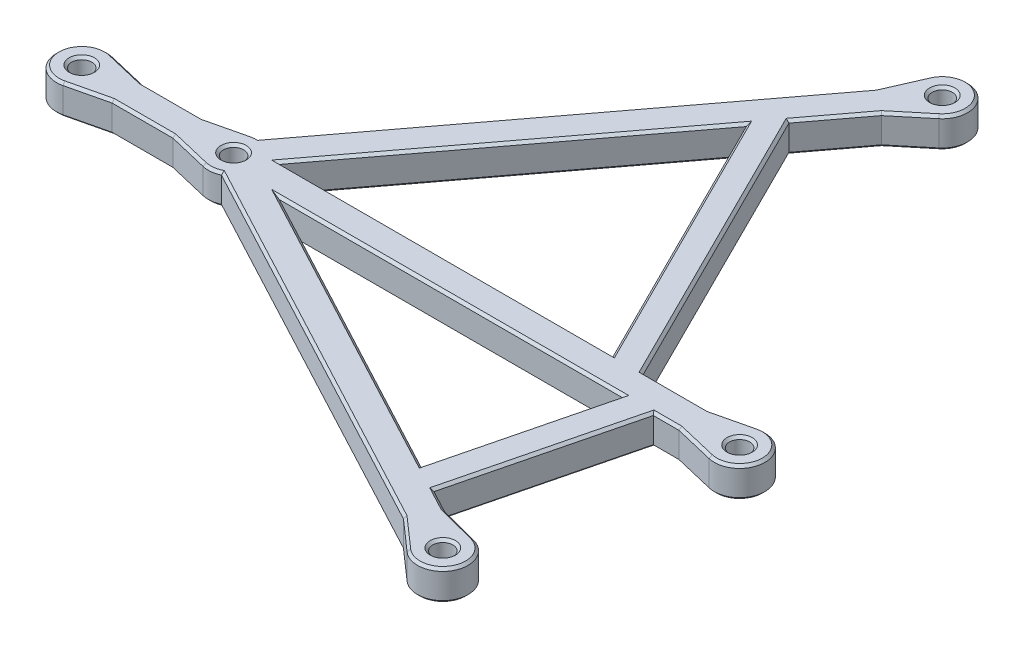
SolidWorks part; units mm, degrees
ref_plane "前视基准面" through (0, 0, 0) normal (0, 0, 1) x (1, 0, 0)
ref_plane "上视基准面" through (0, 0, 0) normal (0, 1, 0) x (1, 0, 0)
ref_plane "右视基准面" through (0, 0, 0) normal (1, 0, 0) x (0, 0, -1)
other "Configuration Table"
sketch "草图1" plane through (0, 0, 0) normal (0, 1, 0) x (1, 0, 0)
  line L0 (0, 0) -> (15, 0) construction
  line L1 (15, 0) -> (65, 0) construction
  line L2 (2, 1.5) -> (13, 1.5)
  line L3 (2, -1.5) -> (13, -1.5)
  line L4 (17, 1.5) -> (63, 1.5)
  line L5 (17, -1.5) -> (63, -1.5)
  arc A0 (2, 1.5) -> (2, -1.5) centre (0, 0) ccw
  arc A1 (17, 1.5) -> (13, 1.5) centre (15, 0) ccw
  arc A2 (63, -1.5) -> (63, 1.5) centre (65, 0) ccw
  arc A3 (13, -1.5) -> (17, -1.5) centre (15, 0) ccw
  circle A4 centre (0, 0) radius 1
  circle A5 centre (15, 0) radius 1
  circle A6 centre (65, 0) radius 1
  dimension "D1" = 5
  dimension "D3" = 5
  dimension "D5" = 5
  dimension "D6" = 2
  dimension "D7" = 2
  dimension "D9" = 2
  dimension "D2" = 15
  dimension "D4" = 50
  dimension "D8" = 3
extrude "凸台-拉伸2" add sketch "草图1" along normal blind 3
sketch "草图3" plane through (0, 0, 0) normal (0, 1, 0) x (1, 0, 0)
  line L0 (15, 0) -> (65, 0) construction
  line L1 (15, 0) -> (45.0908, 39.9318) construction
  line L2 (15, 0) -> (59.1474, -23.4736) construction
  line L3 (15.0057, 2.5) -> (42.6892, 39.2372)
  line L4 (17.4016, 0.6945) -> (45.0851, 37.4318)
  line L5 (16.0617, -2.2634) -> (56.6773, -23.8591)
  line L6 (17.4701, 0.3855) -> (58.0857, -21.2102)
  arc A0 (17.4701, 0.3855) -> (17.4016, 0.6945) centre (15, 0) ccw
  arc A1 (45.0851, 37.4318) -> (42.6892, 39.2372) centre (45.0908, 39.9318) ccw
  arc A2 (56.6773, -23.8591) -> (58.0857, -21.2102) centre (59.1474, -23.4736) ccw
  arc A3 (15.0057, 2.5) -> (16.0617, -2.2634) centre (15, 0) ccw
  circle A4 centre (59.1474, -23.4736) radius 1
  circle A5 centre (45.0908, 39.9318) radius 1
  circle A6 centre (15, 0) radius 1
  dimension "D1" = 5
  dimension "D6" = 5
  dimension "D7" = 5
  dimension "D10" = 2
  dimension "D11" = 2
  dimension "D12" = 2
  dimension "D2" = 53
  dimension "D3" = 28
  dimension "D4" = 50
  dimension "D5" = 50
  dimension "D8" = 3
  dimension "D9" = 3
extrude "凸台-拉伸3" add sketch "草图3" along normal up to surface (3 mm away) up to face at (15, 3, 1)
sketch "草图5" plane through (0, 0, 0) normal (0, 1, 0) x (1, 0, 0)
  line L0 (50.9687, 1.5) -> (37.8445, 27.8232)
  line L1 (63, 1.5) -> (18.0085, 1.5) construction
  line L2 (37.8445, 27.8232) -> (39.6514, 30.221)
  line L3 (39.6514, 30.221) -> (53.9711, 1.5)
  line L4 (50.9687, 1.5) -> (53.9711, 1.5)
  line L5 (18.0085, 1.5) -> (45.0851, 37.4318) construction
  circle A0 centre (15, 0) radius 36 construction
  circle A1 centre (15, 0) radius 39 construction
  dimension "D1" = 72
  dimension "D2" = 78
extrude "凸台-拉伸4" add sketch "草图5" along normal up to surface (3 mm away) up to face at (31.0755, 3, -2.3579)
sketch "草图6" plane through (0, 0, 0) normal (0, 1, 0) x (1, 0, 0)
  line L0 (54.9719, -1.5) -> (50.9973, -17.4412)
  line L1 (50.9973, -17.4412) -> (53.6478, -18.8506)
  line L2 (58.0857, -21.2102) -> (21.0162, -1.5) construction
  line L3 (53.6478, -18.8506) -> (57.9738, -1.5)
  line L4 (57.9738, -1.5) -> (54.9719, -1.5)
  line L5 (21.0162, -1.5) -> (63, -1.5) construction
  circle A0 centre (15, 0) radius 40 construction
  circle A1 centre (15, 0) radius 43 construction
  dimension "D1" = 80
  dimension "D2" = 86
extrude "凸台-拉伸5" add sketch "草图6" along normal up to surface (3 mm away) up to face at (34.0447, 3, -4.2155)
sketch "草图7" plane through (0, 0, 0) normal (0, 1, 0) x (1, 0, 0)
  line L0 (4.5, 1.5) -> (0.5781, 2.4322)
  line L1 (4.5, -1.5) -> (0.5781, -2.4322)
  line L2 (10.5, 1.5) -> (14.4219, 2.4322)
  line L3 (10.5, -1.5) -> (14.4219, -2.4322)
  line L4 (41.1846, 37.2406) -> (42.8003, 40.9338)
  line L5 (43.5805, 35.4352) -> (46.6853, 38.0063)
  line L6 (60.5, -1.5) -> (64.4219, -2.4322)
  line L7 (60.5, 1.5) -> (64.4219, 2.4322)
  line L8 (55.8783, -20.0365) -> (59.7788, -21.0546)
  line L9 (54.4699, -22.6854) -> (57.495, -25.3497)
  line L10 (63, 1.5) -> (53.9711, 1.5)
  line L11 (53.9711, 1.5) -> (39.6514, 30.221)
  line L12 (39.6514, 30.221) -> (45.0851, 37.4318)
  line L13 (42.6892, 39.2372) -> (15.0057, 2.5)
  line L14 (13, 1.5) -> (2, 1.5)
  line L15 (2, -1.5) -> (13, -1.5)
  line L16 (16.0617, -2.2634) -> (56.6773, -23.8591)
  line L17 (58.0857, -21.2102) -> (53.6478, -18.8506)
  line L18 (53.6478, -18.8506) -> (57.9738, -1.5)
  line L19 (57.9738, -1.5) -> (63, -1.5)
  line L20 (63, 1.5) -> (60.5, 1.5)
  line L22 (43.5805, 35.4352) -> (45.0851, 37.4318)
  line L23 (42.6892, 39.2372) -> (41.1846, 37.2406)
  line L24 (13, 1.5) -> (10.5, 1.5)
  line L25 (2, -1.5) -> (4.5, -1.5)
  line L26 (54.4699, -22.6854) -> (56.6773, -23.8591)
  line L27 (58.0857, -21.2102) -> (55.8783, -20.0365)
  line L29 (60.5, -1.5) -> (63, -1.5)
  line L30 (4.5, 1.5) -> (2, 1.5)
  line L31 (10.5, -1.5) -> (13, -1.5)
  arc A0 (0.5781, -2.4322) -> (2, -1.5) centre (0, 0) ccw
  arc A1 (59.7788, -21.0546) -> (58.0857, -21.2102) centre (59.1474, -23.4736) ccw
  arc A2 (42.8003, 40.9338) -> (42.6892, 39.2372) centre (45.0908, 39.9318) ccw
  arc A3 (64.4219, 2.4322) -> (63, 1.5) centre (65, 0) ccw
  arc A6 (45.0851, 37.4318) -> (42.6892, 39.2372) centre (45.0908, 39.9318) ccw
  arc A7 (15.0057, 2.5) -> (13, 1.5) centre (15, 0) ccw
  arc A8 (2, 1.5) -> (2, -1.5) centre (0, 0) ccw
  arc A9 (13, -1.5) -> (16.0617, -2.2634) centre (15, 0) ccw
  arc A10 (56.6773, -23.8591) -> (58.0857, -21.2102) centre (59.1474, -23.4736) ccw
  arc A11 (63, -1.5) -> (63, 1.5) centre (65, 0) ccw
  arc A12 (45.0851, 37.4318) -> (46.6853, 38.0063) centre (45.0908, 39.9318) ccw
  arc A13 (14.4219, 2.4322) -> (13, 1.5) centre (15, 0) ccw
  arc A14 (2, 1.5) -> (0.5781, 2.4322) centre (0, 0) ccw
  arc A15 (13, -1.5) -> (14.4219, -2.4322) centre (15, 0) ccw
  arc A16 (56.6773, -23.8591) -> (57.495, -25.3497) centre (59.1474, -23.4736) ccw
  arc A17 (63, -1.5) -> (64.4219, -2.4322) centre (65, 0) ccw
  dimension "D2" = 2.5
  dimension "D3" = 2.5
  dimension "D4" = 2.5
  dimension "D5" = 2.5
  dimension "D6" = 2.5
  dimension "D7" = 2.5
  dimension "D8" = 2.5
  dimension "D9" = 2.5
  dimension "D10" = 2.5
  dimension "D11" = 2.5
  dimension "D1" = 0
extrude "凸台-拉伸6" add sketch "草图7" along normal up to surface (3 mm away) up to face at (42.3284, 3, 6.8137)
chamfer "倒角1" distance 0.25 angle 45 74 edges at (65, 3, 1) (0, 3, 1) (59.1474, 3, 24.4736) (45.0908, 3, -38.9318) (15, 3, 1) (27.9265, 0, -14.6616) (27.9265, 3, -14.6616) (34.4886, 3, -1.5) (44.4066, 3, -14.6616) (44.4066, 0, -14.6616) (36.0067, 0, 9.4706) (36.0067, 3, 9.4706) (52.9846, 3, 9.4706) (52.9846, 0, 9.4706) (37.994, 3, 1.5) (55.8108, 3, 10.1753) (55.8108, 0, 10.1753) (54.7631, 0, 19.4436) (54.7631, 3, 19.4436) (57.8285, 3, 20.5456) (57.8285, 0, 20.5456) (61.3547, 3, 24.6473) (61.3547, 0, 24.6473) (55.9825, 3, 24.0175) (55.9825, 0, 24.0175) (35.2658, 3, 12.4744) (35.2658, 0, 12.4744) (15.2561, 3, 2.4868) (12.4609, 3, 1.9661) (12.4609, 0, 1.9661) (7.5, 3, 1.5) (2.5391, 3, 1.9661) (2.5391, 0, 1.9661) (-2.5, 3, 0) (2.5391, 3, -1.9661) (2.5391, 0, -1.9661) (7.5, 3, -1.5) (12.4609, 3, -1.9661) (12.4609, 0, -1.9661) (14.7118, 3, -2.4833) (28.0952, 0, -19.8703) (28.0952, 3, -19.8703) (41.9925, 3, -39.0872) (41.9925, 0, -39.0872) (46.5953, 3, -41.9284) (46.5953, 0, -41.9284) (45.1329, 3, -36.7207) (45.1329, 0, -36.7207) (41.616, 0, -32.8281) (41.616, 3, -32.8281) (46.8113, 3, -15.8605) (46.8113, 0, -15.8605) (57.2356, 3, -1.5) (62.4609, 3, -1.9661) (62.4609, 0, -1.9661) (67.5, 3, 0) (62.4609, 3, 1.9661) (62.4609, 0, 1.9661) (59.2369, 3, 1.5) (65, 0, 1) (0, 0, 1) (59.1474, 0, 24.4736) (45.0908, 0, -38.9318) (15, 0, 1) (34.4886, 0, -1.5) (37.994, 0, 1.5) (67.5, 0, 0) (57.2356, 0, -1.5) (14.7118, 0, -2.4833) (7.5, 0, -1.5) (-2.5, 0, 0) (7.5, 0, 1.5) (15.2561, 0, 2.4868) (59.2369, 0, 1.5)
